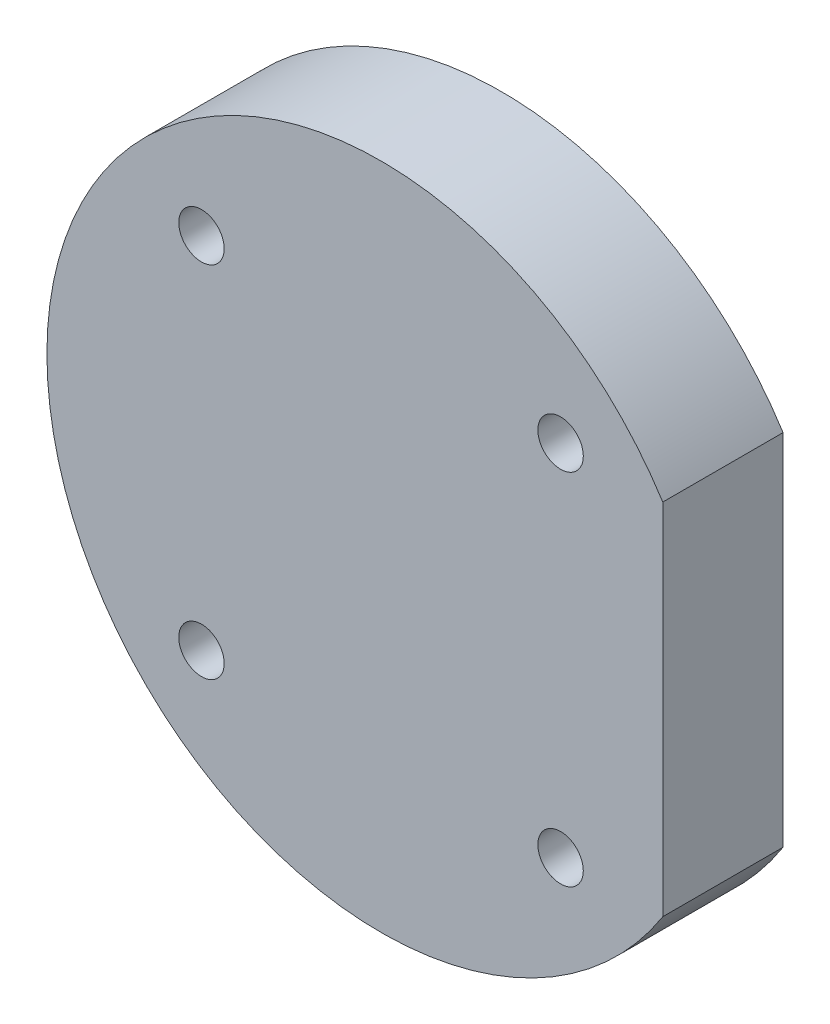
SolidWorks part; units mm, degrees
ref_plane "Plan de face" through (0, 0, 0) normal (0, 0, 1) x (1, 0, 0)
ref_plane "Plan de dessus" through (0, 0, 0) normal (0, 1, 0) x (1, 0, 0)
ref_plane "Plan de droite" through (0, 0, 0) normal (1, 0, 0) x (0, 0, -1)
sketch "Esquisse1" plane through (0, 0, 0) normal (0, 0, 1) x (1, 0, 0)
  circle A0 centre (0, 0) radius 25
  circle A1 centre (-13.435, 13.435) radius 1.7
  circle A2 centre (13.435, 13.435) radius 1.7
  circle A3 centre (13.435, -13.435) radius 1.7
  circle A4 centre (-13.435, -13.435) radius 1.7
  point P19 (0, 0)
  dimension "D1" = 50
  dimension "D5" = 19
  dimension "D6" = 3.4
  dimension "D4" = 4
extrude "Boss.-Extru.1" add sketch "Esquisse1" along normal blind 9
ref_plane "Plan1" through (0, 0, 0) normal (1, 0, 0) x (0, 0, -1)
sketch "Esquisse6" plane through (0, 0, 0) normal (0, 0, -1) x (-1, 0, 0)
  circle A0 centre (0, 0) radius 11
  dimension "D1" = 22
extrude "Enlèv. mat.-Extru.2" cut sketch "Esquisse6" against normal blind 6
fillet "Congé2" radius 0.5 1 edges at (-11, 0, 6)
sketch "Esquisse8" plane through (0, 0, 9) normal (0, 0, 1) x (1, 0, 0)
  line L0 (-6.5, 2) -> (6.5, 2) construction
  line L1 (6.5, 2) -> (6.5, -2) construction
  line L2 (6.5, -2) -> (-6.5, -2) construction
  line L3 (-6.5, 2) -> (-6.5, -2) construction
  line L4 (-6.25, 1.75) -> (-6.25, 2) construction
  line L5 (-6.25, 1.75) -> (-6.5, 1.75) construction
  line L6 (-6.25, -1.75) -> (-6.5, -1.75) construction
  line L7 (-6.25, -1.75) -> (-6.25, -2) construction
  line L8 (6.25, 1.75) -> (6.25, 2) construction
  line L9 (6.25, 1.75) -> (6.5, 1.75) construction
  line L10 (6.25, -1.75) -> (6.5, -1.75) construction
  line L11 (6.25, -1.75) -> (6.25, -2) construction
  line L12 (6.5, 0) -> (-6.5, 0) construction
  circle A0 centre (-6.25, 1.75) radius 0.25
  circle A1 centre (-6.25, -1.75) radius 0.25
  circle A2 centre (6.25, 1.75) radius 0.25
  circle A3 centre (6.25, -1.75) radius 0.25
sketch "Esquisse15" plane through (0, 0, 0) normal (0, 0, -1) x (-1, 0, 0)
  line L1 (-21.0832, 13.435) -> (-29.047, 13.435)
  line L2 (-21.0832, 13.435) -> (-21.0832, -14.015)
  line L3 (-21.0832, -14.015) -> (-29.047, -14.015)
  line L4 (-29.047, 13.435) -> (-29.047, -14.015)
  circle A0 centre (0, 0) radius 25 construction
extrude "Enlèv. mat.-Extru.4" cut sketch "Esquisse15" against normal through all
sketch "Esquisse16" plane through (0, 0, 0) normal (0, 0, -1) x (-1, 0, 0)
  line L0 (6.8997, 0) -> (28.1131, 0) construction
  line L1 (28.1131, -3) -> (6.8997, -3)
  line L2 (28.1131, -3) -> (28.1131, 3)
  line L3 (28.1131, 3) -> (6.8997, 3)
  line L4 (6.8997, -3) -> (6.8997, 3)
  line L5 (-6.5, 0) -> (6.5, 0) construction
extrude "Enlèv. mat.-Extru.5" cut sketch "Esquisse16" against normal blind 6
equation "\"9.5.00mm\"=6"
